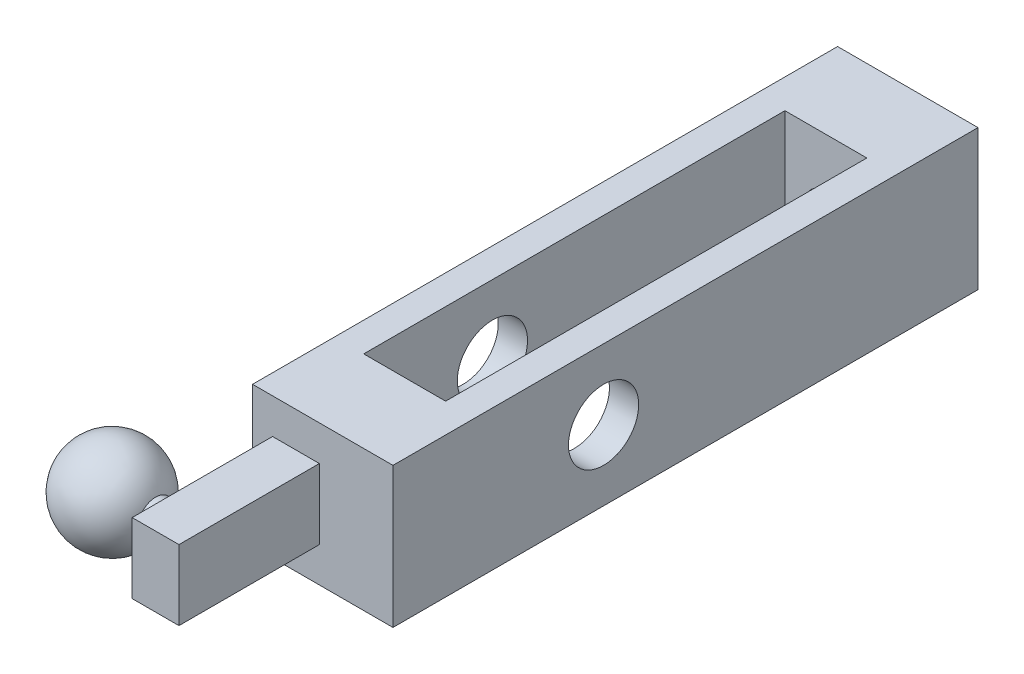
SolidWorks part; units mm, degrees
ref_plane "前视基准面" through (0, 0, 0) normal (0, 0, 1) x (1, 0, 0)
ref_plane "上视基准面" through (0, 0, 0) normal (0, 1, 0) x (1, 0, 0)
ref_plane "右视基准面" through (0, 0, 0) normal (1, 0, 0) x (0, 0, -1)
other "Configuration Table"
sketch "草图1" plane through (0, 0, 0) normal (0, 0, 1) x (1, 0, 0)
  line L1 (3, -3) -> (-3, -3)
  line L2 (3, -3) -> (3, 3)
  line L3 (3, 3) -> (-3, 3)
  line L4 (-3, -3) -> (-3, 3)
  line L5 (3, -3) -> (-3, 3) construction
  line L6 (3, 3) -> (-3, -3) construction
  point P0 (0, 0)
  dimension "D1" = 6
  dimension "D2" = 6
extrude "凸台-拉伸1" add sketch "草图1" along normal blind 25
sketch "草图2" plane through (0, 0, 25) normal (0, 0, 1) x (1, 0, 0)
  line L1 (-2.1448, 1.4955) -> (-0.1448, 1.4955)
  line L2 (-2.1448, 1.4955) -> (-2.1448, -1.5045)
  line L3 (-2.1448, -1.5045) -> (-0.1448, -1.5045)
  line L4 (-0.1448, 1.4955) -> (-0.1448, -1.5045)
  line L5 (-2.1448, 1.4955) -> (-0.1448, -1.5045) construction
  line L6 (-2.1448, -1.5045) -> (-0.1448, 1.4955) construction
  point P0 (-1.1448, -0.0045)
  point P6 (0, 0)
  point P7 (0, 0)
  point P8 (0, 0)
  point P9 (0, 0)
  dimension "D1" = 2
  dimension "D2" = 3
extrude "凸台-拉伸2" add sketch "草图2" along normal blind 6
sketch "草图3" plane through (-2.1448, 0, 0) normal (-1, 0, 0) x (0, 0, 1)
  circle A0 centre (29, 0) radius 0.75
  dimension "D1" = 1.5
  dimension "D2" = 29
extrude "凸台-拉伸3" add sketch "草图3" along normal blind 1
sketch "草图4" plane through (0, 0, 0) normal (0, 1, 0) x (1, 0, 0)
  line L0 (-3.1448, -29) -> (-6.9988, -29)
  line L1 (-3.1448, -28.25) -> (-3.1448, -29.75) construction
  line L2 (-3.1448, -29) -> (-3.1448, -28.25)
  arc A0 (-3.1448, -28.25) -> (-6.9988, -29) centre (-4.9988, -29) ccw
  dimension "D1" = 4
revolve "旋转1" add sketch "草图4" angle 360 about L0
sketch "草图5" plane through (0.5, 3, 0) normal (0, -1, 0) x (0, 0, 1)
  line L0 (25, 3.5) -> (0, 3.5) construction
  line L1 (3.5, 2.25) -> (21.5, 2.25)
  line L2 (3.5, 2.25) -> (3.5, -1.25)
  line L3 (3.5, -1.25) -> (21.5, -1.25)
  line L4 (21.5, 2.25) -> (21.5, -1.25)
  point P4 (3.5, 0.5)
  point P8 (12.5, 3.5)
  point P9 (12.5, 2.25)
  dimension "D1" = 18
  dimension "D2" = 3.5
extrude "切除-拉伸1" cut sketch "草图5" along normal blind 8
sketch "草图6" plane through (-3, 0, 0) normal (-1, 0, 0) x (0, 0, 1)
  line L0 (0, 3) -> (0, -3) construction
  circle A0 centre (16, 0) radius 1.5
  dimension "D1" = 3
  dimension "D2" = 16
extrude "切除-拉伸2" cut sketch "草图6" against normal blind 8
sketch "草图7" plane through (0, 0, 0) normal (0, 0, -1) x (-1, 0, 0)
  circle A0 centre (0, 0) radius 0.9
  dimension "D1" = 1.8
extrude "切除-拉伸3" cut sketch "草图7" against normal blind 8
